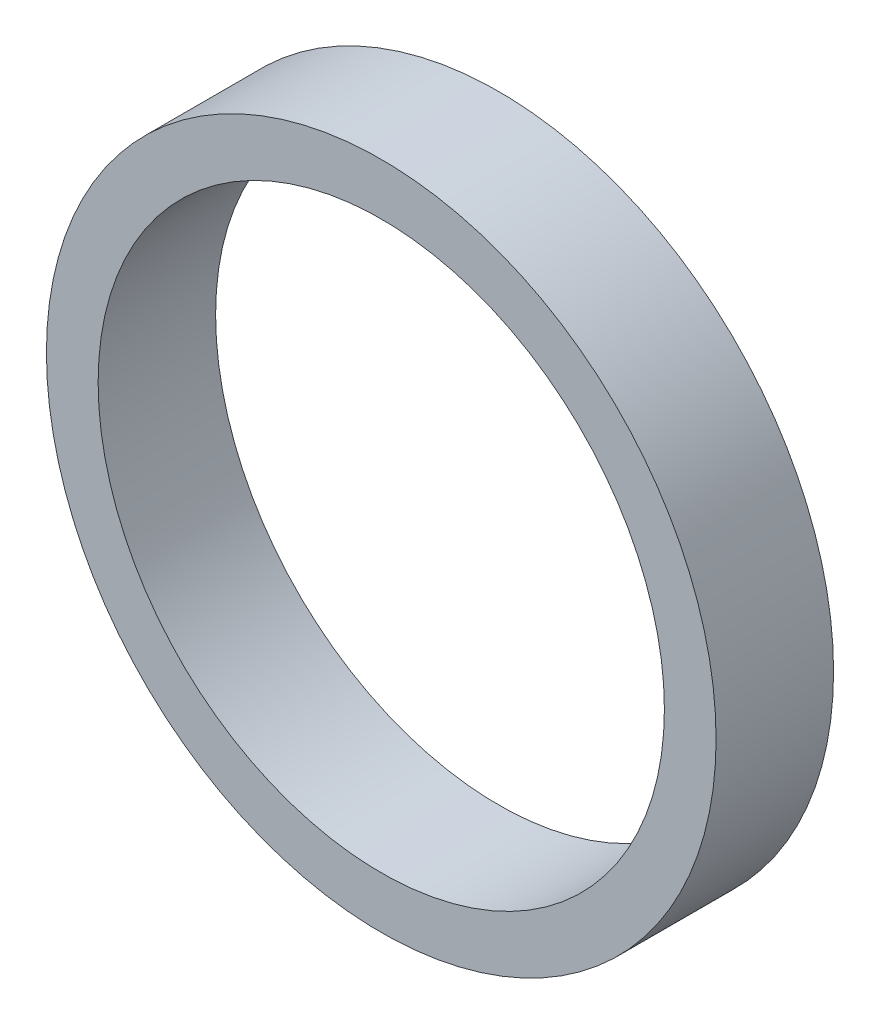
SolidWorks part; units mm, degrees
ref_plane "정면" through (0, 0, 0) normal (0, 0, 1) x (1, 0, 0)
ref_plane "윗면" through (0, 0, 0) normal (0, 1, 0) x (1, 0, 0)
ref_plane "우측면" through (0, 0, 0) normal (1, 0, 0) x (0, 0, -1)
sketch "스케치1" plane through (0, 0, 0) normal (0, 0, 1) x (1, 0, 0)
  circle A0 centre (0, 0) radius 12.05
  circle A1 centre (0, 0) radius 14.25
  dimension "D1" = 24.1
  dimension "D2" = 28.5
extrude "보스-돌출1" add sketch "스케치1" along normal blind 5
